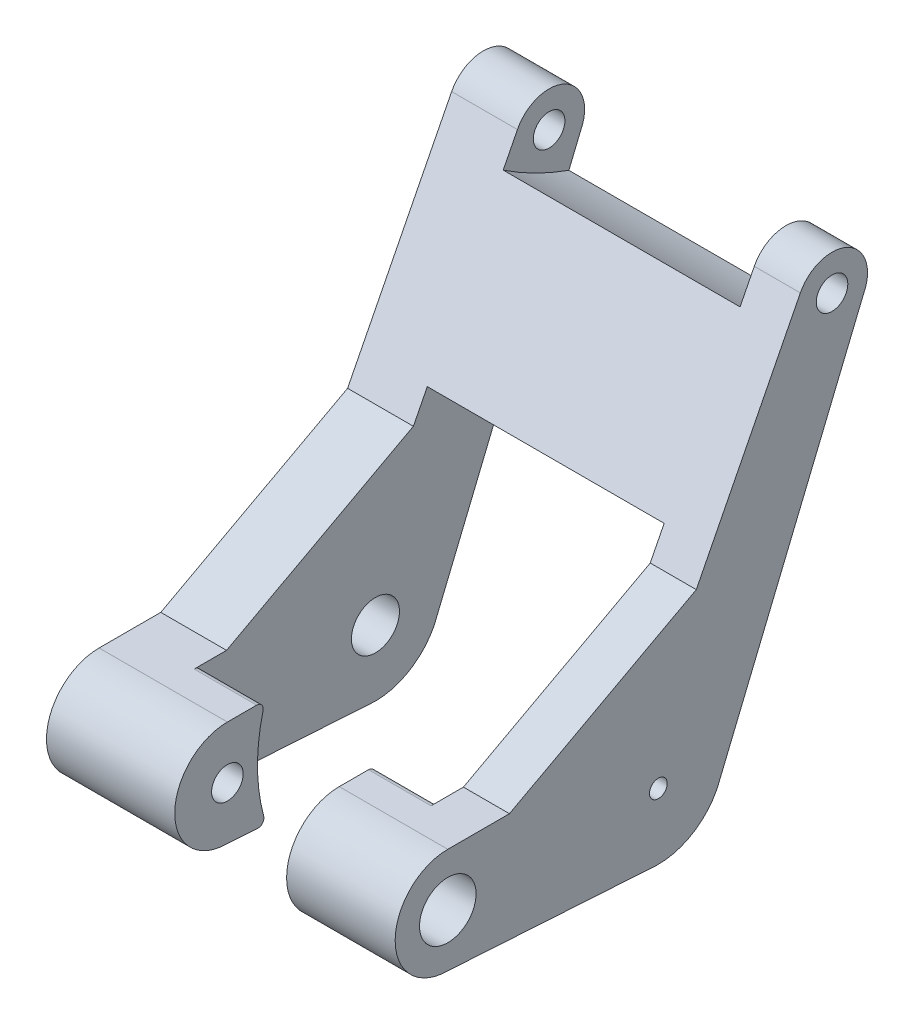
SolidWorks part; units mm, degrees
ref_plane "Front Plane" through (0, 0, 0) normal (0, 0, 1) x (1, 0, 0)
ref_plane "Top Plane" through (0, 0, 0) normal (0, 1, 0) x (1, 0, 0)
ref_plane "Right Plane" through (0, 0, 0) normal (1, 0, 0) x (0, 0, -1)
sketch "Sketch19" plane through (0, 0, 0) normal (1, 0, 0) x (0, 0, -1)
  line L0 (-32, 0) -> (0, 0) construction
  line L5 (0, 0) -> (26.4, 52) construction
  line L8 (-32, -8) -> (0, -10)
  line L12 (-22.6274, 8) -> (-32, 8)
  line L13 (26.4, 52) -> (11.2632, 59.6848) construction
  line L14 (26.4, 52) -> (42.6148, 43.7679) construction
  line L15 (21.585, 54.4445) -> (5.771, 23.2958)
  line L16 (5.771, 23.2958) -> (-22.6274, 8)
  line L17 (0, 0) -> (32.4983, -16.4992) construction
  line L18 (8.9166, -4.5269) -> (31.215, 49.5555)
  arc A2 (-32, -8) -> (-32, 8) centre (-32, 0) cw
  circle A3 centre (26.4, 52) radius 2.4
  circle A4 centre (0, 0) radius 3.65
  circle A5 centre (-32, 0) radius 2.4
  circle A6 centre (0, 0) radius 24 construction
  arc A8 (21.585, 54.4445) -> (31.215, 49.5555) centre (26.4, 52) cw
  arc A9 (0, -10) -> (8.9166, -4.5269) centre (0, 0) ccw
  point P0 (0, 0)
  point P1 (-32, 0)
  point P2 (26.4, 52)
  dimension "D3" = 32
  dimension "D9" = 5.4
  dimension "D10" = 90
  dimension "D11" = 7.3
  dimension "D12" = 4.8
  dimension "D13" = 4.8
  dimension "D14" = 10
  dimension "D5" = 26.4
  dimension "D6" = 90
  dimension "D7" = 8
  dimension "D8" = 90
  dimension "D15" = 48
  dimension "D2" = 52
  dimension "D4" = 0
  dimension "D16" = 31.1487
  dimension "D17" = 15.814
  dimension "D18" = 28.3985
extrude "Base" add sketch "Sketch19" along normal blind 10
sketch "Sketch20" plane through (10, 0, 0) normal (1, 0, 0) x (0, 0, -1)
  line L2 (-22.6274, 8) -> (-32, 8) construction
  line L3 (-32, -8) -> (0, -10) construction
  line L9 (-27.5495, 8) -> (-32, 8)
  line L11 (-32, -8) -> (-27.0863, -8.3071)
  line L12 (21.585, 54.4445) -> (5.771, 23.2958) construction
  line L13 (8.9166, -4.5269) -> (31.215, 49.5555) construction
  line L14 (26.4, 52) -> (44.7669, 88.1772) construction
  line L15 (19.4226, 50.1852) -> (7.8858, 27.4614)
  line L16 (19.4226, 20.9542) -> (29.4061, 45.1682)
  arc A2 (-26.5803, 6.7537) -> (-26.4855, -7.1166) centre (0, 0) ccw
  arc A7 (-26.4855, -7.1166) -> (-27.0863, -8.3071) centre (-27.4512, -7.3761) cw
  arc A13 (-32, 8) -> (-32, -8) centre (-32, 0) ccw
  arc A14 (-32, 8) -> (-32, -8) centre (-32, 0) ccw construction
  arc A15 (-27.5495, 8) -> (-26.5803, 6.7537) centre (-27.5495, 7) cw
  circle A16 centre (0, 0) radius 26.0089 construction
  arc A17 (7.8858, 27.4614) -> (19.4226, 20.9542) centre (0, 0) cw
  arc A19 (19.4226, 50.1852) -> (29.4061, 45.1682) centre (44.7669, 88.1772) ccw
  point P23 (-26.2322, 8)
  point P30 (-26.2322, 8)
  point P33 (-27.0863, -8.3071)
  dimension "D3" = 1
  dimension "D8" = 1
extrude "Connector" add sketch "Sketch20" along normal blind 36
sketch "Sketch21" plane through (46, 0, 0) normal (1, 0, 0) x (0, 0, -1)
  line L0 (19.4226, 50.1852) -> (7.8858, 27.4614) construction
  line L1 (29.4061, 45.1682) -> (31.215, 49.5555) construction
  line L2 (19.4226, 20.9542) -> (29.4061, 45.1682) construction
  line L3 (5.771, 23.2958) -> (-22.6274, 8) construction
  line L4 (-27.0863, -8.3071) -> (0, -10) construction
  line L12 (-22.6274, 8) -> (-27.5401, 8)
  line L13 (-27.5401, 8) -> (-32, 8)
  line L14 (-32, -8) -> (-26.7435, -8.3285)
  line L15 (-26.7435, -8.3285) -> (-0.1967, -9.9877)
  line L16 (8.9166, -4.5269) -> (19.4226, 20.9542)
  line L17 (19.4226, 20.9542) -> (27.1437, 39.6809)
  line L18 (27.1437, 39.6809) -> (31.215, 49.5555)
  line L19 (21.585, 54.4445) -> (17.5952, 46.5859)
  line L20 (17.5952, 46.5859) -> (5.771, 23.2958)
  line L21 (5.771, 23.2958) -> (0, 20.1875)
  line L22 (0, 20.1875) -> (-22.6274, 8)
  arc A3 (-32, 8) -> (-32, -8) centre (-32, 0) ccw
  arc A4 (-0.1967, -9.9877) -> (8.9166, -4.5269) centre (0.0052, 0.0103) ccw
  arc A5 (31.215, 49.5555) -> (21.585, 54.4445) centre (26.4, 52) ccw
  circle A6 centre (26.4, 52) radius 2.4
  circle A7 centre (-32, 0) radius 2.4
  circle A8 centre (0.0052, 0.0103) radius 1.35
  point P3 (37.3946, 52)
  point P9 (37, 52)
  point P11 (17.5952, 46.5859)
  point P15 (5.771, 23.2958)
  point P17 (0, 0)
  point P18 (0, 0)
  point P20 (26.4, 52)
  point P21 (21.585, 54.4445)
  point P23 (31.1162, 49.3158)
  point P28 (27.1437, 39.6809)
  point P33 (19.4226, 20.9542)
  point P35 (0, 20.1875)
  point P44 (8.9166, -4.5269)
  point P46 (-0.1967, -9.9877)
  dimension "D1" = 4.8
  dimension "D2" = 4.8
  dimension "D3" = 2.7
extrude "ThinPlate" add sketch "Sketch21" along normal blind 7
sketch "Sketch22" plane through (46, 0, 0) normal (-1, 0, 0) x (0, 0, 1)
  circle A0 centre (-0.0052, 0.0103) radius 1.35
  circle A1 centre (-0.0052, 0.0103) radius 3
  dimension "D1" = 6
  dimension "D2" = 2.7
extrude "Spacer" add sketch "Sketch22" along normal blind 6
sketch "Sketch23" plane through (0, 8, 0) normal (0, 1, 0) x (1, 0, 0)
  line L0 (10, -26.4512) -> (46, -26.4512) construction
  line L1 (46, -26.4512) -> (46, -40) construction
  line L2 (0, -40) -> (53, -40) construction
  line L3 (46, -40) -> (10, -40) construction
  line L4 (10, -40) -> (10, -26.4512) construction
  line L5 (28, -26.4512) -> (28, -40) construction
  line L6 (53, -32) -> (0, -32) construction
  line L7 (10, -32) -> (46, -32) construction
  line L8 (19.5, -32) -> (19.5, -40.5)
  line L9 (19.5, -23.5) -> (36.5, -23.5) construction
  line L10 (19.5, -23.5) -> (19.5, -40.5) construction
  line L11 (19.5, -40.5) -> (36.5, -40.5) construction
  line L12 (36.5, -23.5) -> (36.5, -40.5) construction
  line L13 (19.5, -40.5) -> (36.5, -40.5)
  line L14 (36.5, -40.5) -> (36.5, -32)
  line L15 (19.5, -32) -> (19.5, -23.5)
  line L16 (19.5, -23.5) -> (36.5, -23.5)
  line L17 (36.5, -23.5) -> (36.5, -32)
  point P12 (46, -32)
  point P13 (28, -32)
  point P14 (10, -32)
  dimension "D1" = 17
  dimension "D2" = 17
  dimension "D3" = 8.5
  dimension "D4" = 8.5
extrude "ShockHole" cut sketch "Sketch23" against normal through all
sketch "Sketch25" plane through (0, 0, 0) normal (-1, 0, 0) x (0, 0, 1)
  circle A0 centre (32, 0) radius 2.4
extrude "ShockScrewHole" cut sketch "Sketch25" against normal through all
sketch "Sketch26" plane through (53, 0, 0) normal (1, 0, 0) x (0, 0, -1)
  circle A0 centre (-32, 0) radius 4.3
  dimension "D1" = 8.6
extrude "BoltMount" cut sketch "Sketch26" against normal blind 8.6
sketch "Sketch27" plane through (0, 0, 0) normal (-1, 0, 0) x (0, 0, 1)
  line L1 (35.298, -2.8942) -> (36.1555, 1.409)
  line L2 (36.1555, 1.409) -> (32.8575, 4.3033)
  line L3 (32.8575, 4.3033) -> (28.702, 2.8942)
  line L4 (28.702, 2.8942) -> (27.8445, -1.409)
  line L5 (27.8445, -1.409) -> (31.1425, -4.3033)
  line L6 (31.1425, -4.3033) -> (35.298, -2.8942)
  circle A0 centre (32, 0) radius 3.8 construction
  dimension "D1" = 7.6
extrude "NutMount" cut sketch "Sketch27" against normal blind 8
sketch "Sketch28" plane through (53, 0, 0) normal (1, 0, 0) x (0, 0, -1)
  line L0 (31.8, 52) -> (31.8, -13.3188) construction
  line L1 (-40, 0) -> (-40, -13.3188) construction
  line L2 (-40, -13.3188) -> (31.8, -13.3188) construction
  line L3 (26.4, 52) -> (26.4, -13.3188) construction
  line L4 (-32, 0) -> (-32, -13.3188) construction
  arc A0 (31.215, 49.5555) -> (21.585, 54.4445) centre (26.4, 52) ccw construction
  arc A1 (-32, 8) -> (-32, -8) centre (-32, 0) ccw construction
  arc A2 (31.215, 49.5555) -> (21.585, 54.4445) centre (26.4, 52) ccw construction
  circle A3 centre (26.4, 52) radius 2.4 construction
  dimension "D1" = 58.4
sketch "Sketch29" plane through (0, 8, 0) normal (0, 1, 0) x (1, 0, 0)
  line L0 (0, -22.6274) -> (0, -32) construction
  line L1 (53, -22.6274) -> (53, -32) construction
  line L2 (0, -27.3137) -> (53, -27.3137) construction
  line L3 (36.5, -29.7748) -> (36.5, -27.3137) construction
  line L4 (36.5, -32) -> (36.5, -27.5495) construction
  line L5 (19.5, -29.7748) -> (19.5, -27.3137) construction
  line L6 (19.5, -27.5495) -> (19.5, -32) construction
  dimension "D1" = 53
  dimension "D2" = 16.5
  dimension "D3" = 19.5
